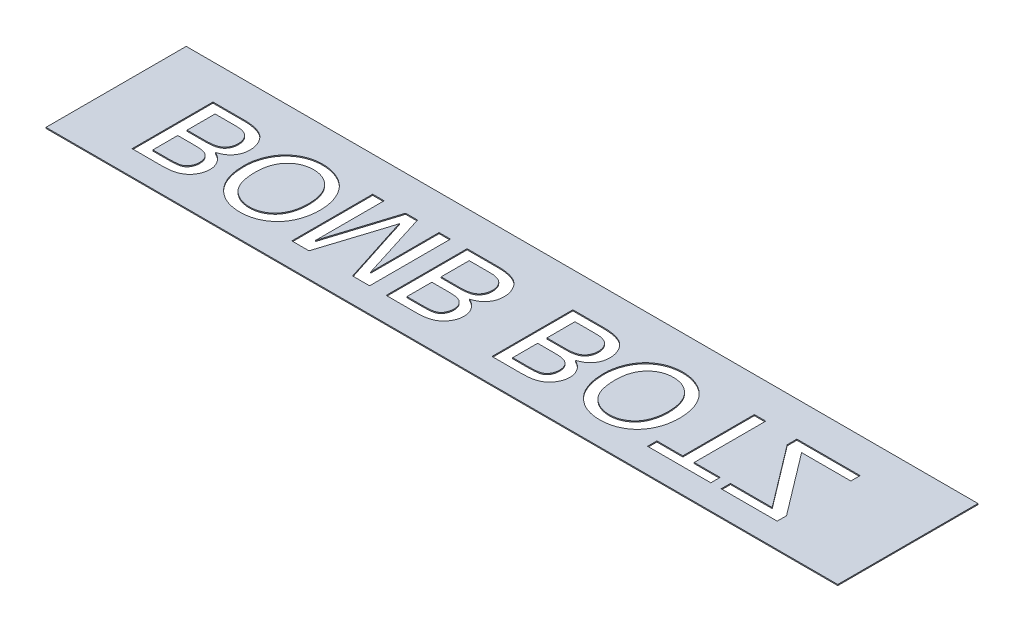
SolidWorks part; units mm, degrees
ref_plane "Front Plane" through (0, 0, 0) normal (0, 0, 1) x (1, 0, 0)
ref_plane "Top Plane" through (0, 0, 0) normal (0, 1, 0) x (1, 0, 0)
ref_plane "Right Plane" through (0, 0, 0) normal (1, 0, 0) x (0, 0, -1)
sketch "Sketch1" plane through (0, 0, 0) normal (0, 1, 0) x (1, 0, 0)
  line L1 (1219.2, -215.9) -> (-1219.2, -215.9)
  line L2 (1219.2, -215.9) -> (1219.2, 215.9)
  line L3 (1219.2, 215.9) -> (-1219.2, 215.9)
  line L4 (-1219.2, -215.9) -> (-1219.2, 215.9)
  line L5 (1219.2, -215.9) -> (-1219.2, 215.9) construction
  line L6 (1219.2, 215.9) -> (-1219.2, -215.9) construction
  point P0 (0, 0)
  dimension "D1" = 2438.4
  dimension "D2" = 431.8
extrude "Boss-Extrude1" add sketch "Sketch1" along normal mid plane 3.175 contours L2 L3 L4 L1
sketch "Sketch6" plane through (0, -1.5875, 0) normal (0, -1, 0) x (1, 0, 0)
  text T0 "BOMB BOTZ" font "Arial" height in points 970
  point P1 (0, 0)
extrude "Cut-Extrude1" cut sketch "Sketch6" against normal through all both and the other way through all
